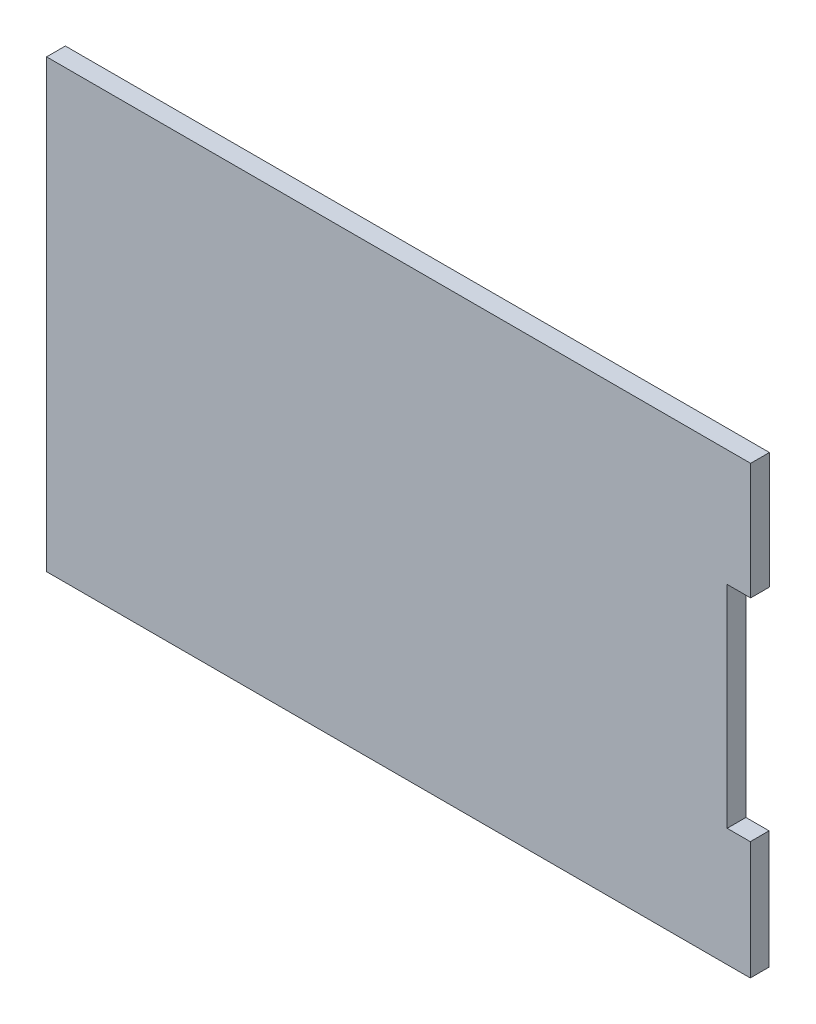
SolidWorks part; units mm, degrees
ref_plane "前视基准面" through (0, 0, 0) normal (0, 0, 1) x (1, 0, 0)
ref_plane "上视基准面" through (0, 0, 0) normal (0, 1, 0) x (1, 0, 0)
ref_plane "右视基准面" through (0, 0, 0) normal (1, 0, 0) x (0, 0, -1)
other "Configuration Table"
sketch "草图1" plane through (0, 0, 0) normal (0, 0, 1) x (1, 0, 0)
  line L1 (-19.55, 12.7) -> (19.55, 12.7)
  line L2 (-19.55, 12.7) -> (-19.55, -12.7)
  line L3 (-19.55, -12.7) -> (19.55, -12.7)
  line L4 (19.55, 12.7) -> (19.55, -12.7)
  line L5 (-19.55, 12.7) -> (19.55, -12.7) construction
  line L6 (-19.55, -12.7) -> (19.55, 12.7) construction
  point P0 (0, 0)
  dimension "D1" = 39.1
  dimension "D2" = 25.4
extrude "凸台-拉伸1" add sketch "草图1" along normal blind 0.3
sketch "草图2" plane through (0, 0, 0.3) normal (0, 0, 1) x (1, 0, 0)
  line L0 (23.55, 9.0683) -> (23.55, 19.0048)
  line L5 (-36.45, -18.9952) -> (23.5199, -18.9952)
  line L6 (-36.45, -18.9952) -> (-36.45, 19.0048)
  line L7 (-36.45, 19.0048) -> (23.55, 19.0048)
  line L9 (-36.45, -18.9952) -> (23.55, 19.0048) construction
  line L11 (-1000, 0) -> (49000, 0) construction
  line L12 (-36.45, 19.0048) -> (23.5199, -18.9952) construction
  line L13 (23.5199, -8.9317) -> (23.5199, -18.9952)
  line L15 (23.55, 9.0683) -> (21.55, 9.0683)
  line L17 (23.5199, -8.9317) -> (21.55, -8.9317)
  line L18 (21.55, 9.0683) -> (21.55, -8.9317)
  line L19 (23.55, 9.0683) -> (21.55, -8.9317) construction
  line L20 (23.5199, -8.9317) -> (21.55, 9.0683) construction
  point P0 (-6.4575, 0)
  point P12 (22.5424, 0)
  dimension "D1" = 38
  dimension "D3" = 60
  dimension "D4" = 2
  dimension "D5" = 18
extrude "凸台-拉伸2" add sketch "草图2" along normal blind 1.6 separate body
sketch "草图3" plane through (0, 0, 0.3) normal (0, 0, -1) x (-1, 0, 0)
  line L0 (36.45, 19.0048) -> (36.45, -18.9952) construction
  line L1 (22.45, 13.5048) -> (28.45, 13.5048)
  line L2 (22.45, 13.5048) -> (22.45, 7.5048)
  line L3 (22.45, 7.5048) -> (28.45, 7.5048)
  line L4 (28.45, 13.5048) -> (28.45, 7.5048)
  line L5 (22.45, 13.5048) -> (28.45, 7.5048) construction
  line L6 (22.45, 7.5048) -> (28.45, 13.5048) construction
  line L7 (22.45, 3.0048) -> (28.45, 3.0048)
  line L8 (22.45, 3.0048) -> (22.45, -2.9952)
  line L9 (22.45, -2.9952) -> (28.45, -2.9952)
  line L10 (28.45, 3.0048) -> (28.45, -2.9952)
  line L11 (22.45, 3.0048) -> (28.45, -2.9952) construction
  line L12 (22.45, -2.9952) -> (28.45, 3.0048) construction
  line L13 (22.45, -7.4952) -> (28.45, -7.4952)
  line L14 (22.45, -7.4952) -> (22.45, -13.4952)
  line L15 (22.45, -13.4952) -> (28.45, -13.4952)
  line L16 (28.45, -7.4952) -> (28.45, -13.4952)
  line L17 (22.45, -7.4952) -> (28.45, -13.4952) construction
  line L18 (22.45, -13.4952) -> (28.45, -7.4952) construction
  line L19 (36.45, -18.9952) -> (-23.5199, -18.9952) construction
  line L20 (-23.55, 19.0048) -> (36.45, 19.0048) construction
  line L21 (-1000, 0) -> (49000, 0) construction
  point P0 (25.45, 10.5048)
  point P5 (25.45, 0.0048)
  point P10 (25.45, -10.4952)
  dimension "D1" = 6
  dimension "D2" = 6
  dimension "D3" = 6
  dimension "D4" = 6
  dimension "D5" = 6
  dimension "D6" = 6
  dimension "D7" = 4.5
  dimension "D8" = 5.5
  dimension "D9" = 5.5
  dimension "D10" = 8
extrude "凸台-拉伸3" add sketch "草图3" along normal blind 5
